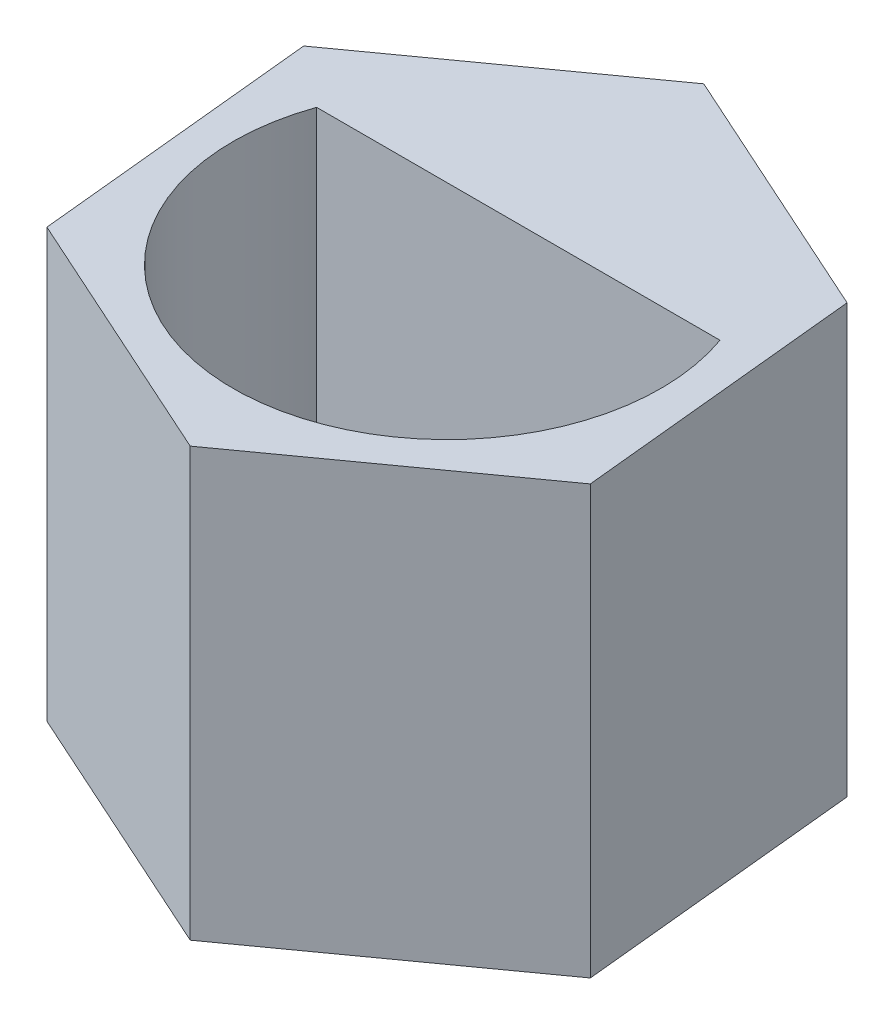
SolidWorks part; units mm, degrees
ref_plane "Front Plane" through (0, 0, 0) normal (0, 0, 1) x (1, 0, 0)
ref_plane "Top Plane" through (0, 0, 0) normal (0, 1, 0) x (1, 0, 0)
ref_plane "Right Plane" through (0, 0, 0) normal (1, 0, 0) x (0, 0, -1)
sketch "Sketch1" plane through (0, 0, 0) normal (0, 1, 0) x (1, 0, 0)
  line L0 (-1.4142, 0.5) -> (1.4142, 0.5)
  line L2 (1.8319, -0.8271) -> (1.6322, 1.1729)
  line L3 (1.6322, 1.1729) -> (-0.1996, 2)
  line L4 (-0.1996, 2) -> (-1.8319, 0.8271)
  line L5 (-1.8319, 0.8271) -> (-1.6322, -1.1729)
  line L6 (-1.6322, -1.1729) -> (0.1996, -2)
  line L7 (0.1996, -2) -> (1.8319, -0.8271)
  arc A0 (-1.4142, 0.5) -> (1.4142, 0.5) centre (0, 0) ccw
  circle A1 centre (0, 0) radius 1.7407 construction
  dimension "D1" = 3
  dimension "D2" = 0.5
  dimension "D3" = 2
extrude "Boss-Extrude1" add sketch "Sketch1" along normal blind 3
